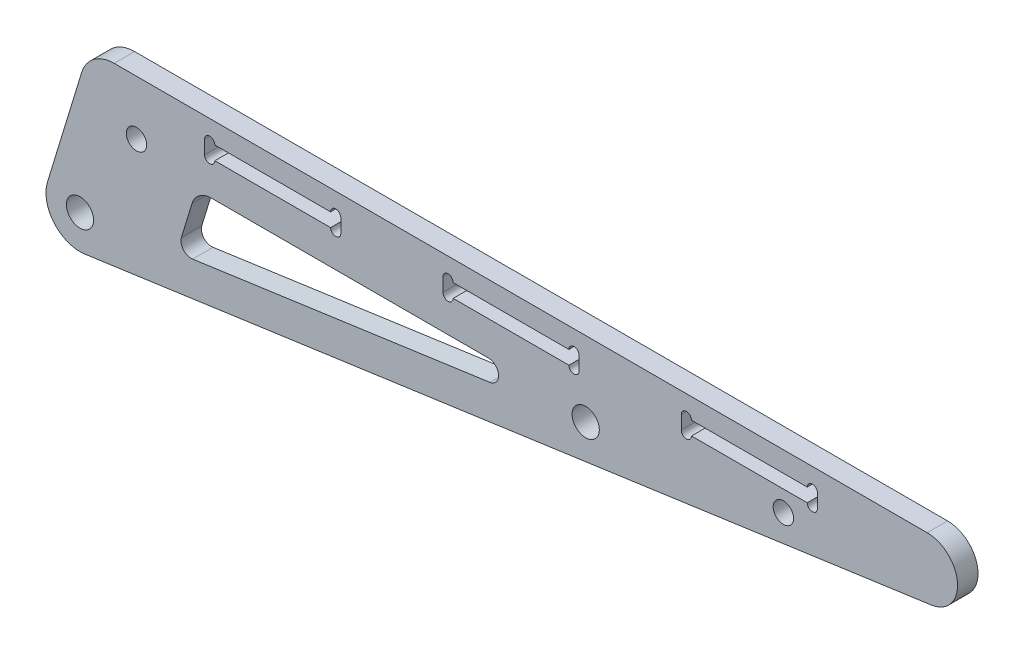
SolidWorks part; units mm, degrees
material "Thornel Mat VMA"
ref_plane "前视基准面" through (0, 0, 0) normal (0, 0, 1) x (1, 0, 0)
ref_plane "上视基准面" through (0, 0, 0) normal (0, 1, 0) x (1, 0, 0)
ref_plane "右视基准面" through (0, 0, 0) normal (1, 0, 0) x (0, 0, -1)
sketch "草图1" plane through (0, 0, 0) normal (0, 0, 1) x (1, 0, 0)
  line L0 (0, 0) -> (-59.0345, 10.7206)
  line L2 (0, 0.25) -> (-136.5, 0.25) construction
  line L5 (-133.3, 0.25) -> (-4.5731, 18.399)
  dimension "D1" = 130
  dimension "D2" = 136.5
  dimension "D3" = 60
  dimension "D4" = 133.3
  dimension "D5" = 55
  dimension "D6" = 0.25
sketch "草图2" plane through (0, 0, 0) normal (0, 0, 1) x (1, 0, 0)
  line L2 (-132.602, -4.701) -> (-8.2677, 12.8286)
  line L3 (-131.9738, 21.7206) -> (-8.8914, 21.7206)
  line L4 (-131.9738, 21.7206) -> (-138.0822, 1.7098)
  line L6 (-133.3, 0.25) -> (-4.5731, 18.399) construction
  line L7 (-80, 18.7206) -> (-80, 16.7206)
  line L8 (-115, 18.7206) -> (-95, 18.7206)
  line L9 (-115, 18.7206) -> (-115, 16.7206)
  line L10 (-115, 16.7206) -> (-95, 16.7206)
  line L11 (-95, 18.7206) -> (-95, 16.7206)
  line L12 (-80, 18.7206) -> (-60, 18.7206)
  line L13 (-60, 18.7206) -> (-60, 16.7206)
  line L14 (-80, 16.7206) -> (-60, 16.7206)
  line L15 (-45, 18.7206) -> (-45, 16.7206)
  line L16 (-45, 18.7206) -> (-25, 18.7206)
  line L17 (-25, 18.7206) -> (-25, 16.7206)
  line L18 (-45, 16.7206) -> (-25, 16.7206)
  line L19 (-125, 13.7206) -> (-30, 13.7206) construction
  circle A7 centre (-59.0345, 10.7206) radius 2
  circle A9 centre (-133.3, 0.25) radius 2
  arc A11 (-8.2677, 12.8286) -> (-8.8914, 21.7206) centre (-8.8914, 17.2527) ccw
  arc A12 (-138.0822, 1.7098) -> (-132.602, -4.701) centre (-133.3, 0.25) ccw
  circle A13 centre (-125, 13.7206) radius 1.5
  circle A14 centre (-30, 13.7206) radius 1.5
  dimension "D1" = 5
  dimension "D2" = 2
  dimension "D3" = 20
  dimension "D4" = 3
  dimension "D6" = 4
  dimension "D7" = 15
  dimension "D10" = 6
  dimension "D11" = 3
  dimension "D12" = 3
  dimension "D13" = 10
  dimension "D14" = 95
  dimension "D5" = 3
  dimension "D8" = 25
  dimension "D9" = 65
extrude "凸台-拉伸1" add sketch "草图2" along normal blind 3
sketch "草图3" plane through (0, 0, 3) normal (0, 0, 1) x (1, 0, 0)
  line L0 (-95, 18.7206) -> (-115, 18.7206) construction
  line L1 (-115, 16.7206) -> (-95, 16.7206) construction
  line L2 (-60, 18.7206) -> (-80, 18.7206) construction
  line L6 (-116.8548, 9.5964) -> (-118.4091, 4.5045)
  line L7 (-116.7651, 2.5812) -> (-73.1159, 8.7352)
  line L8 (-73.3253, 11.7206) -> (-113.9855, 11.7206)
  line L9 (-132.602, -4.701) -> (-8.2677, 12.8286) construction
  line L10 (-131.9738, 21.7206) -> (-138.0822, 1.7098) construction
  circle A0 centre (-114.25, 18.7206) radius 0.75
  circle A1 centre (-114.25, 16.7206) radius 0.75
  circle A2 centre (-95.75, 18.7206) radius 0.75
  circle A3 centre (-95.75, 16.7206) radius 0.75
  circle A4 centre (-79.25, 18.7206) radius 0.75
  circle A5 centre (-79.25, 16.7206) radius 0.75
  circle A6 centre (-60.75, 18.7206) radius 0.75
  circle A7 centre (-60.75, 16.7206) radius 0.75
  circle A8 centre (-44.25, 18.7206) radius 0.75
  circle A9 centre (-44.25, 16.7206) radius 0.75
  circle A10 centre (-25.75, 18.7206) radius 0.75
  circle A11 centre (-25.75, 16.7206) radius 0.75
  arc A14 (-73.1159, 8.7352) -> (-73.3253, 11.7206) centre (-73.3253, 10.2206) ccw
  arc A15 (-116.8548, 9.5964) -> (-113.9855, 11.7206) centre (-113.9855, 8.7206) cw
  arc A16 (-116.7651, 2.5812) -> (-118.4091, 4.5045) centre (-116.9745, 4.0665) cw
  dimension "D1" = 1.5
  dimension "D3" = 1.5
  dimension "D7" = 3
  dimension "D8" = 1.5
  dimension "D4" = 5
  dimension "D5" = 5
  dimension "D6" = 18
  dimension "D2" = 3
extrude "切除-拉伸1" cut sketch "草图3" against normal through all
fillet "圆角1" radius 5 1 edges at (-131.9738, 21.7206, 1.5)
